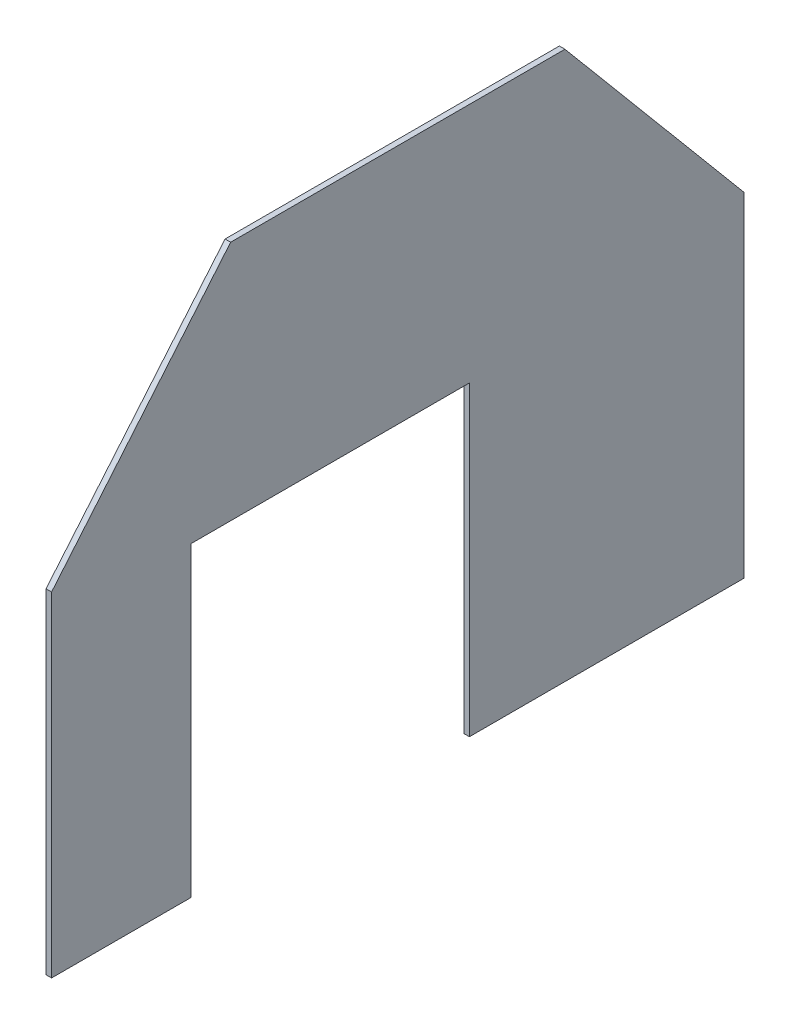
SolidWorks part; units mm, degrees
ref_plane "前视基准面" through (0, 0, 0) normal (0, 0, 1) x (1, 0, 0)
ref_plane "上视基准面" through (0, 0, 0) normal (0, 1, 0) x (1, 0, 0)
ref_plane "右视基准面" through (0, 0, 0) normal (1, 0, 0) x (0, 0, -1)
sketch "草图1" plane through (0, 0, 0) normal (1, 0, 0) x (0, 0, -1)
  line L0 (0, 0) -> (0, 60)
  line L1 (0, 60) -> (32.1394, 98.3022)
  line L2 (32.1394, 98.3022) -> (92.1394, 98.3022)
  line L4 (124.2788, 60) -> (124.2788, 0)
  line L5 (124.2788, 0) -> (0, 0)
  line L6 (92.1394, 98.3022) -> (124.2788, 60)
  dimension "D1" = 140
  dimension "D2" = 140
  dimension "D3" = 60
  dimension "D4" = 50
  dimension "D5" = 50
  dimension "D6" = 60
extrude "凸台-拉伸1" add sketch "草图1" against normal blind 1
sketch "草图2" plane through (0, 0, 0) normal (1, 0, 0) x (0, 0, -1)
  line L1 (25, 55) -> (25, 0)
  line L2 (75, 55) -> (75, 0)
  line L3 (0, 60) -> (0, 0) construction
  line L4 (25, 0) -> (75, 0)
  line L5 (0, 0) -> (124.2788, 0) construction
  line L6 (25, 55) -> (75, 55)
  dimension "D1" = 25
  dimension "D2" = 75
  dimension "D3" = 55
extrude "切除-拉伸1" cut sketch "草图2" against normal blind 1
